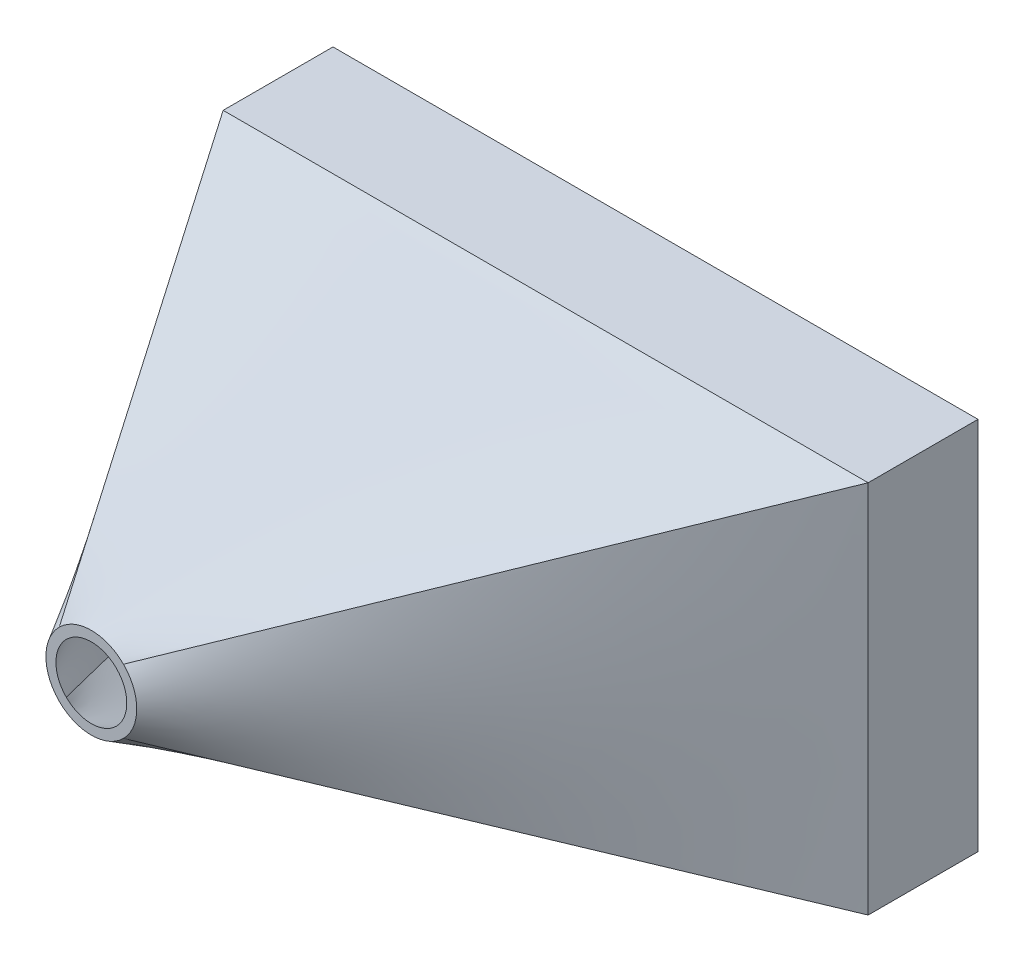
SolidWorks part; units mm, degrees
ref_plane "前视基准面" through (0, 0, 0) normal (0, 0, 1) x (1, 0, 0)
ref_plane "上视基准面" through (0, 0, 0) normal (0, 1, 0) x (1, 0, 0)
ref_plane "右视基准面" through (0, 0, 0) normal (1, 0, 0) x (0, 0, -1)
sketch "草图1" plane through (0, 0, 0) normal (0, 0, 1) x (1, 0, 0)
  line L1 (-62.6, 35.5) -> (62.6, 35.5)
  line L2 (-62.6, 35.5) -> (-62.6, -35.5)
  line L3 (-62.6, -35.5) -> (62.6, -35.5)
  line L4 (62.6, 35.5) -> (62.6, -35.5)
  line L5 (-62.6, 35.5) -> (62.6, -35.5) construction
  line L6 (-62.6, -35.5) -> (62.6, 35.5) construction
  line L7 (-64.6, 37.5) -> (64.6, 37.5)
  line L8 (-64.6, 37.5) -> (-64.6, -37.5)
  line L9 (-64.6, -37.5) -> (64.6, -37.5)
  line L10 (64.6, 37.5) -> (64.6, -37.5)
  line L11 (-64.6, 37.5) -> (64.6, -37.5) construction
  line L12 (-64.6, -37.5) -> (64.6, 37.5) construction
  point P0 (0, 0)
  point P6 (0, 0)
  dimension "D1" = 125.2
  dimension "D2" = 71
  dimension "D3" = 129.2
  dimension "D4" = 75
extrude "凸台-拉伸1" add sketch "草图1" along normal blind 22
ref_plane "基准面1" through (0, 0, 96) normal (0, 0, 1) x (1, 0, 0)
ref_plane "基准面2" through (0, 0, 22) normal (0, 0, 1) x (1, 0, 0)
sketch "草图2" plane through (0, 0, 22) normal (0, 0, 1) x (1, 0, 0)
  line L0 (-64.6, 37.5) -> (-62.6, 35.5)
  line L1 (-62.6, 35.5) -> (62.6, 35.5)
  line L2 (62.6, 35.5) -> (64.6, 37.5)
  line L3 (64.6, 37.5) -> (-64.6, 37.5)
sketch "草图3" plane through (0, 0, 22) normal (0, 0, 1) x (1, 0, 0)
  line L0 (-62.6, 35.5) -> (-64.6, 37.5)
  line L1 (-64.6, 37.5) -> (-64.6, -37.5)
  line L2 (-64.6, -37.5) -> (-62.6, -35.5)
  line L3 (-62.6, -35.5) -> (-62.6, 35.5)
sketch "草图4" plane through (0, 0, 22) normal (0, 0, 1) x (1, 0, 0)
  line L0 (-62.6, -35.5) -> (-64.6, -37.5)
  line L1 (-64.6, -37.5) -> (64.6, -37.5)
  line L2 (64.6, -37.5) -> (62.6, -35.5)
  line L3 (62.6, -35.5) -> (-62.6, -35.5)
sketch "草图5" plane through (0, 0, 22) normal (0, 0, 1) x (1, 0, 0)
  line L0 (64.6, 37.5) -> (62.6, 35.5)
  line L1 (62.6, 35.5) -> (62.6, -35.5)
  line L2 (62.6, -35.5) -> (64.6, -37.5)
  line L3 (64.6, -37.5) -> (64.6, 37.5)
ref_plane "基准面3" through (0, -35.5, 0) normal (0, 1, 0) x (1, 0, 0)
sketch "草图6" plane through (0, 0, 96) normal (0, 0, 1) x (1, 0, 0)
  line L0 (0, 0) -> (50000, 0) construction
  line L1 (0, 0) -> (0, -50000) construction
  line L2 (-17, -1) -> (35338.3391, -35356.3391) construction
  line L3 (-17, -1) -> (-35372.3391, -35356.3391) construction
  line L4 (-22.0205, 4.0205) -> (-23.4347, 5.4347)
  line L5 (-11.9795, 4.0205) -> (-10.5653, 5.4347)
  arc A0 (-11.9795, 4.0205) -> (-22.0205, 4.0205) centre (-17, -1) ccw
  arc A1 (-10.5653, 5.4347) -> (-23.4347, 5.4347) centre (-17, -1) ccw
  point P5 (-17, -1)
  point P10 (-22.0205, 4.0205)
  point P11 (-23.4347, 5.4347)
  point P12 (-10.5653, 5.4347)
  point P13 (-11.9795, 4.0205)
  dimension "D1" = 17
  dimension "D2" = 1
  dimension "D3" = 7.1
  dimension "D4" = 9.1
sketch "草图7" plane through (0, 0, 96) normal (0, 0, 1) x (1, 0, 0)
  line L0 (141404.3562, 141420.3562) -> (-176793.6953, -176777.6953) construction
  line L1 (-22.0205, 4.0205) -> (-23.4347, 5.4347) construction
  line L2 (-22.0205, 4.0205) -> (-23.4347, 5.4347)
  line L3 (-23.4347, -7.4347) -> (-22.0205, -6.0205)
  arc A0 (-22.0205, 4.0205) -> (-22.0205, -6.0205) centre (-17, -1) ccw
  arc A1 (-23.4347, -7.4347) -> (-23.4347, 5.4347) centre (-17, -1) cw
  point P0 (-22.0205, -6.0205)
  point P1 (-23.4347, -7.4347)
sketch "草图8" plane through (0, 0, 96) normal (0, 0, 1) x (1, 0, 0)
  line L0 (-141438.3562, 141420.3562) -> (176759.6953, -176777.6953) construction
  line L1 (-22.0205, -6.0205) -> (-23.4347, -7.4347)
  line L2 (-11.9795, -6.0205) -> (-10.5653, -7.4347)
  arc A0 (-22.0205, -6.0205) -> (-11.9795, -6.0205) centre (-17, -1) ccw
  arc A1 (-23.4347, -7.4347) -> (-10.5653, -7.4347) centre (-17, -1) ccw
  point P0 (-11.9795, -6.0205)
  point P1 (-10.5653, -7.4347)
sketch "草图9" plane through (0, 0, 96) normal (0, 0, 1) x (1, 0, 0)
  line L0 (-11.9795, 4.0205) -> (-10.5653, 5.4347) construction
  line L1 (-10.5653, 5.4347) -> (-11.9795, 4.0205)
  line L2 (-11.9795, -6.0205) -> (-10.5653, -7.4347)
  arc A0 (-11.9795, -6.0205) -> (-11.9795, 4.0205) centre (-17, -1) ccw
  arc A1 (-11.9795, 4.0205) -> (-22.0205, 4.0205) centre (-17, -1) ccw construction
  arc A2 (-10.5653, -7.4347) -> (-10.5653, 5.4347) centre (-17, -1) ccw
loft "放样1" add profiles "草图2", "草图6"
loft "放样2" add profiles "草图3", "草图7"
loft "放样3" add profiles "草图4", "草图8"
loft "放样4" add profiles "草图5", "草图9"
sketch "草图11" plane through (0, -35.5, 0) normal (0, 1, 0) x (1, 0, 0)
  line L0 (-62.6, 0) -> (62.6, 0)
  line L1 (62.6, -22) -> (62.6, 0) construction
  line L2 (62.6, 0) -> (62.6, -22)
  line L3 (62.6, -22) -> (-62.6, -22)
  line L4 (-62.6, -22) -> (-62.6, 0)
extrude "切除-拉伸1" cut sketch "草图11" against normal blind 10
